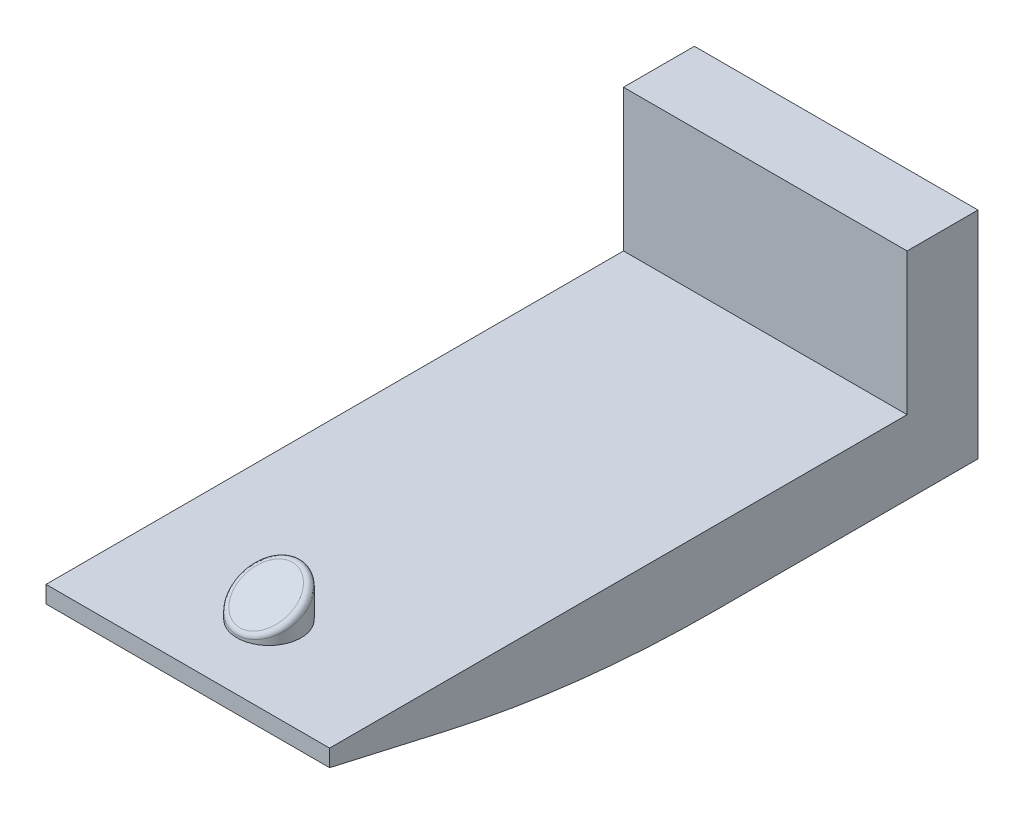
SolidWorks part; units mm, degrees
ref_plane "Front Plane" through (0, 0, 0) normal (0, 0, 1) x (1, 0, 0)
ref_plane "Top Plane" through (0, 0, 0) normal (0, 1, 0) x (1, 0, 0)
ref_plane "Right Plane" through (0, 0, 0) normal (1, 0, 0) x (0, 0, -1)
sketch "Sketch1" plane through (0, 0, 0) normal (1, 0, 0) x (0, 0, -1)
  line L0 (-32.385, 0) -> (0, 0)
  line L1 (0, 0) -> (0, 9.652)
  line L2 (0, 9.652) -> (-3.175, 9.652)
  line L3 (-3.175, 9.652) -> (-3.175, 3.302)
  line L4 (-3.175, 3.302) -> (-32.385, 3.302)
  line L5 (-32.385, 3.302) -> (-32.385, 0)
  line L6 (-29.0357, 3.302) -> (-29.0357, 2.54)
  line L7 (-32.385, 4.8006) -> (-32.385, 1.3716)
  line L8 (-32.385, 1.3716) -> (-23.9, 1.3716)
  line L9 (-23.9, 1.3716) -> (-23.9, 4.8006)
  line L10 (-23.9, 4.8006) -> (-32.385, 4.8006)
  line L11 (-25.4, 3.302) -> (-25.4, 4.8006) construction
  line L12 (-23.9, 4.8006) -> (-23.9, 3.302) construction
  line L13 (-32.385, 3.302) -> (-23.9, 1.3716)
  circle A1 centre (-3.175, 3.302) radius 1.016
  arc A2 (-11.6883, 0) -> (-23.9, 1.3716) centre (-11.6883, 55.0476) cw
  dimension "D5" = 2.032
  dimension "D3" = 3.175
  dimension "D1" = 3.302
  dimension "D2" = 29.21
  dimension "D4" = 6.35
  dimension "D7" = 1.4986
  dimension "D8" = 3.429
  dimension "D10" = 1.5
  dimension "D6" = 0.762
  dimension "D9" = 22.225
extrude "Boss-Extrude1" add sketch "Sketch1" along normal blind 12.7
sketch "Sketch2" plane through (0, 3.302, 0) normal (0, 1, 0) x (1, 0, 0)
  line L0 (12.7, -3.175) -> (0, -3.175) construction
  line L4 (12.7, -32.385) -> (0, -32.385) construction
  circle A0 centre (6.35, -25.4) radius 1.4351
  point P5 (6.35, -32.385)
  dimension "D1" = 2.8702
  dimension "D2" = 22.225
extrude "Boss-Extrude2" add sketch "Sketch2" along normal blind 3.81
sketch "Sketch3" plane through (12.7, 0, 0) normal (1, 0, 0) x (0, 0, -1)
  line L0 (-26.8351, 3.556) -> (-23.9649, 5.207)
  line L1 (-23.9649, 3.302) -> (-23.9649, 7.112) construction
  line L2 (-23.9649, 5.207) -> (-23.9649, 7.112)
  line L3 (-23.9649, 7.112) -> (-26.8351, 7.112)
  line L4 (-26.8351, 7.112) -> (-26.8351, 3.556)
  line L5 (-26.8351, 7.112) -> (-26.8351, 3.302) construction
  line L6 (-3.175, 3.302) -> (-32.385, 3.302) construction
  point P7 (0, 0)
  point P10 (-26.8351, 3.569)
  dimension "D1" = 0.254
extrude "Cut-Extrude1" cut sketch "Sketch3" against normal through all contours L4 L0 L2 L3
fillet "Fillet1" radius 0.254 1 edges at (6.35, 3.556, 26.8351)
fillet "Fillet2" [suppressed] radius 1.27
equation "\"WallThickness\"=0.125"
equation "\"D9@Sketch1\"=\"WallThickness\"+.75"
equation "\"D2@Sketch2\"=\"WallThickness\"+.75"
